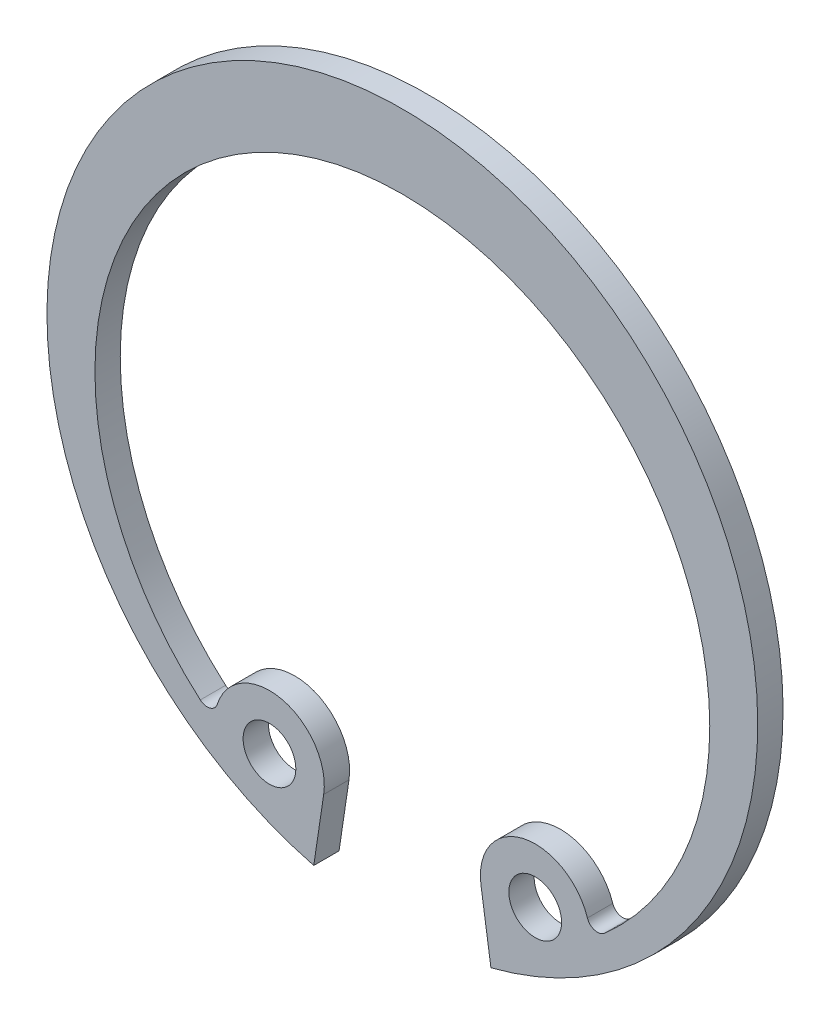
SolidWorks part; units mm, degrees
ref_plane "Front Plane" through (0, 0, 0) normal (0, 0, 1) x (1, 0, 0)
ref_plane "Top Plane" through (0, 0, 0) normal (0, 1, 0) x (1, 0, 0)
ref_plane "Right Plane" through (0, 0, 0) normal (1, 0, 0) x (0, 0, -1)
sketch "Sketch1" plane through (0, 0, 0) normal (0, 0, 1) x (1, 0, 0)
  line L0 (0, 0) -> (0, 16.85) construction
  line L1 (-3.7289, -13.1657) -> (-4.2, -16.3182)
  line L2 (3.7289, -13.1657) -> (4.2, -16.3182)
  line L3 (5.1506, -10.4496) -> (7.4496, -15.1138) construction
  arc A0 (4.2, -16.3182) -> (-4.2, -16.3182) centre (0, 0) ccw
  arc A1 (-9.5796, -12.2096) -> (-8.775, -11.9858) centre (-9.251, -11.8328) ccw
  circle A2 centre (-6.3, -12.7814) radius 1.25
  circle A3 centre (6.3, -12.7814) radius 1.25
  circle A4 centre (0, 0) radius 10.5 construction
  arc A6 (-3.7289, -13.1657) -> (-8.775, -11.9858) centre (-6.3, -12.7814) ccw
  arc A7 (8.775, -11.9858) -> (3.7289, -13.1657) centre (6.3, -12.7814) ccw
  arc A8 (9.5796, -12.2096) -> (-9.5796, -12.2096) centre (0, -1.225) ccw
  arc A9 (9.5796, -12.2096) -> (8.775, -11.9858) centre (9.251, -11.8328) cw
  point P13 (0, 13.35)
  dimension "D1" = 0.5
  dimension "RIC_D2_s" = 33.7
  dimension "D2" = 17
  dimension "RIC_D4_s" = 29.15
  dimension "RIC_D0_s" = 2.5
  dimension "RIC_D5_s" = 21
  dimension "RIC_B_s" = 3.5
  dimension "RIC_MSM_2" = 12.6
  dimension "RIC_MSM_1" = 8.4
  dimension "RIC_A_s" = 5.2
extrude "Boss-Extrude1" add sketch "Sketch1" along normal blind 1.2
equation "\"RIC_D4_s@Sketch1\"=\"RIC_D2_s@Sketch1\"-1.3*\"RIC_B_s@Sketch1\""
